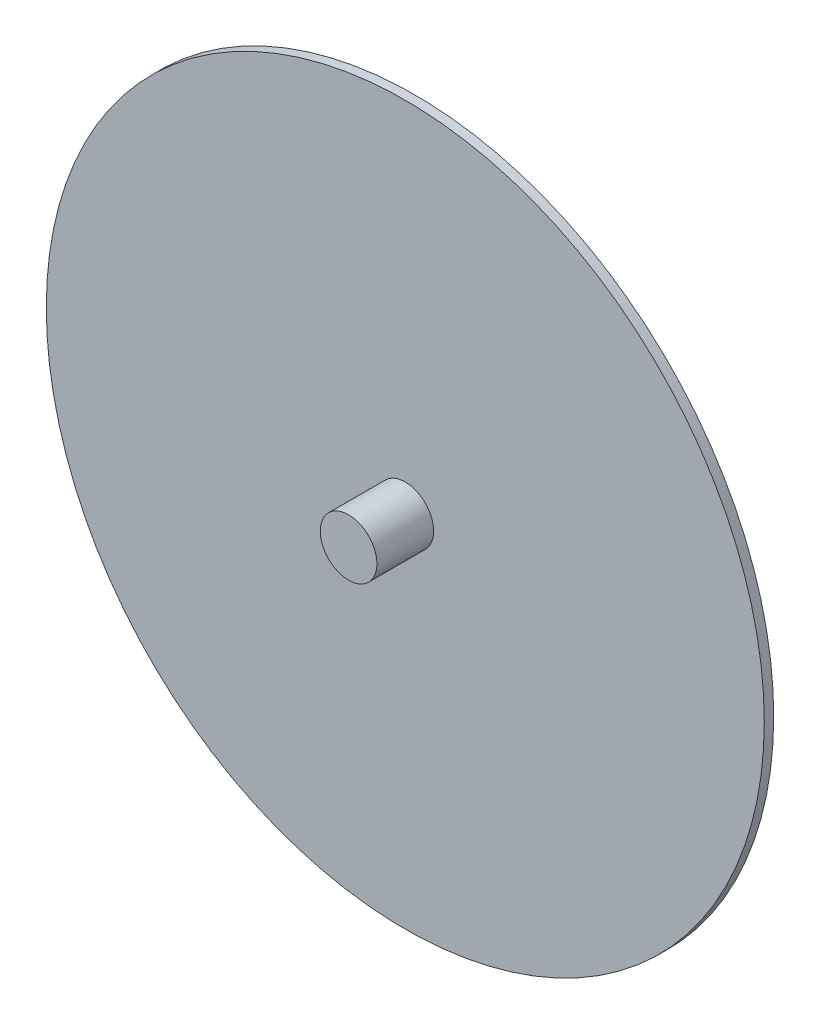
SolidWorks part; units mm, degrees
ref_plane "前视基准面" through (0, 0, 0) normal (0, 0, 1) x (1, 0, 0)
ref_plane "上视基准面" through (0, 0, 0) normal (0, 1, 0) x (1, 0, 0)
ref_plane "右视基准面" through (0, 0, 0) normal (1, 0, 0) x (0, 0, -1)
sketch "草图1" plane through (0, 0, 0) normal (0, 0, 1) x (1, 0, 0)
  circle A0 centre (0, 0) radius 380
  dimension "D1" = 760
extrude "凸台-拉伸1" add sketch "草图1" along normal blind 10
sketch "草图2" plane through (0, 0, 10) normal (0, 0, 1) x (1, 0, 0)
  circle A0 centre (0, 0) radius 30
  dimension "D1" = 60
extrude "凸台-拉伸2" add sketch "草图2" along normal blind 60
